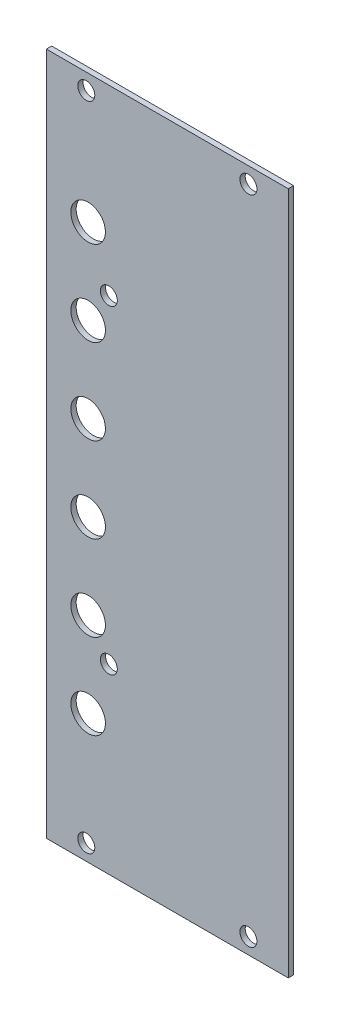
SolidWorks part; units mm, degrees
ref_plane "Front Plane" through (0, 0, 0) normal (0, 0, 1) x (1, 0, 0)
ref_plane "Top Plane" through (0, 0, 0) normal (0, 1, 0) x (1, 0, 0)
ref_plane "Right Plane" through (0, 0, 0) normal (1, 0, 0) x (0, 0, -1)
sketch "Sketch2" plane through (0, 0, 0) normal (0, 0, 1) x (1, 0, 0)
  line L0 (7.5, 125.5) -> (7.5, 128.5) construction
  line L1 (0, 0) -> (45.48, 0)
  line L2 (0, 0) -> (0, 128.5)
  line L3 (0, 128.5) -> (45.48, 128.5)
  line L4 (45.48, 0) -> (45.48, 128.5)
  line L5 (7.5, 125.5) -> (37.98, 125.5) construction
  line L6 (7.5, 125.5) -> (7.5, 3) construction
  line L7 (7.5, 3) -> (37.98, 3) construction
  line L8 (37.98, 125.5) -> (37.98, 3) construction
  line L9 (7.5, 3) -> (7.5, 0) construction
  line L10 (7.5, 125.5) -> (0, 125.5) construction
  line L11 (37.98, 125.5) -> (45.48, 125.5) construction
  circle A0 centre (7.5, 125.5) radius 1.6
  circle A1 centre (37.98, 125.5) radius 1.6
  circle A2 centre (37.98, 3) radius 1.6
  circle A3 centre (7.5, 3) radius 1.6
  dimension "D5" = 3.2
  dimension "D1" = 3
  dimension "D2" = 7.5
  dimension "D3" = 128.5
  dimension "D4" = 30.48
extrude "Boss-Extrude1" add sketch "Sketch2" along normal blind 1 contours L1 L4 L3 L2 A3 A2 A1 A0
sketch "Sketch3" plane through (0, 0, 1) normal (0, 0, 1) x (1, 0, 0)
  line L1 (0, 0) -> (0, 128.5) construction
  line L2 (0, 128.5) -> (45.48, 128.5) construction
  circle A0 centre (7.85, 104.25) radius 3.25
  circle A1 centre (7.85, 88.25) radius 3.25
  circle A2 centre (7.85, 72.25) radius 3.25
  circle A3 centre (7.85, 56.25) radius 3.25
  circle A4 centre (7.85, 40.25) radius 3.25
  circle A5 centre (7.85, 24.25) radius 3.25
  point P0 (7.85, 104.25)
  dimension "D5" = 6.5
  dimension "D1" = 7.85
  dimension "D2" = 24.25
  dimension "D4" = 16
  dimension "D3" = 6
extrude "sma_cuts" cut sketch "Sketch3" against normal through all both and the other way through all
sketch "Sketch4" plane through (0, 0, 1) normal (0, 0, 1) x (1, 0, 0)
  line L0 (0, 0) -> (0, 128.5) construction
  line L1 (0, 128.5) -> (45.48, 128.5) construction
  circle A0 centre (11.7314, 94.225) radius 1.6
  circle A1 centre (11.7314, 34.225) radius 1.6
  point P6 (11.7314, 34.225)
  point P7 (0, 0)
  point P8 (0, 0)
  point P13 (11.7314, 94.225)
  point P14 (0, 0)
  dimension "D1" = 60
  dimension "D4" = 3.2
  dimension "D2" = 11.7314
  dimension "D3" = 34.275
extrude "mounting_bracket_cuts" cut sketch "Sketch4" against normal through all both and the other way through all
